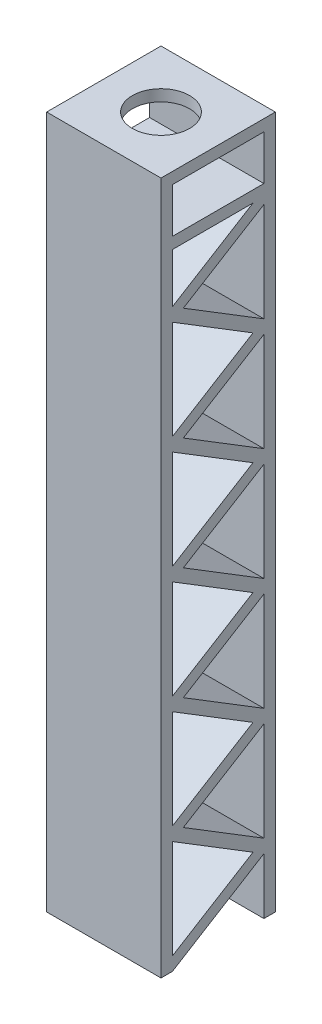
SolidWorks part; units mm, degrees
material "Corrugated Paper"
ref_plane "Front Plane" through (0, 0, 0) normal (0, 0, 1) x (1, 0, 0)
ref_plane "Top Plane" through (0, 0, 0) normal (0, 1, 0) x (1, 0, 0)
ref_plane "Right Plane" through (0, 0, 0) normal (1, 0, 0) x (0, 0, -1)
sketch "Sketch1" plane through (0, 0, 0) normal (1, 0, 0) x (0, 0, -1)
  line L0 (0, 135.6426) -> (0, -180.6532) construction
  line L2 (-25, -150) -> (-25, 150)
  line L3 (-25, 150) -> (25, 150)
  line L4 (25, -150) -> (25, 150)
  line L5 (15.2254, 120.4167) -> (-20, 120.4167)
  line L8 (-20, -147.0656) -> (-20, -103.7674)
  line L10 (20, -150) -> (20, -128.3511)
  line L11 (-20, -97.8986) -> (-20, -54.6008)
  line L13 (-20, 125.4167) -> (20, 125.4167)
  line L14 (-20, 125.4167) -> (-20, 145)
  line L15 (-20, 145) -> (20, 145)
  line L16 (20, 125.4167) -> (20, 145)
  line L23 (20, -73.3157) -> (20, -30.0179)
  line L26 (-20, 98.7678) -> (15.2254, 120.4167)
  line L27 (15.2254, 71.2497) -> (-20, 92.899)
  line L28 (-20, 49.6012) -> (15.2254, 71.2497)
  line L29 (15.2254, 22.0831) -> (-20, 43.7324)
  line L30 (-20, 0.4346) -> (15.2254, 22.0831)
  line L31 (15.2254, -27.0835) -> (-20, -5.4342)
  line L32 (-20, -48.732) -> (15.2254, -27.0835)
  line L33 (15.2254, -76.2501) -> (-20, -54.6008)
  line L34 (15.2254, -76.2501) -> (-20, -97.8986)
  line L35 (-20, -103.7674) -> (15.2254, -125.4167)
  line L36 (15.2254, -125.4167) -> (-20, -147.0656)
  line L38 (-15.2254, 95.8334) -> (20, 117.4819)
  line L39 (20, 74.1841) -> (-15.2254, 95.8334)
  line L40 (-15.2254, 46.6668) -> (20, 68.3153)
  line L41 (20, 25.0175) -> (-15.2254, 46.6668)
  line L42 (-15.2254, -2.4998) -> (20, 19.1487)
  line L43 (20, -24.1491) -> (-15.2254, -2.4998)
  line L44 (-15.2254, -51.6664) -> (20, -30.0179)
  line L45 (20, -73.3157) -> (-15.2254, -51.6664)
  line L46 (20, -79.1845) -> (-15.2254, -100.833)
  line L47 (-15.2254, -100.833) -> (20, -122.4823)
  line L48 (20, -128.3511) -> (-18.691, -152.1299)
  line L49 (-18.691, -152.1299) -> (-20, -152.9344)
  line L50 (-20, -152.9344) -> (-25, -152.9344)
  line L51 (-25, -152.9344) -> (-25, -150)
  line L53 (0, 199.6954) -> (0, 150) construction
  line L54 (20, -150) -> (20, -152.9344)
  line L55 (20, -152.9344) -> (25, -152.9344)
  line L56 (25, -152.9344) -> (25, -150)
  line L59 (20, -122.4823) -> (20, -79.1845)
  line L68 (-20, -48.732) -> (-20, -5.4342)
  line L69 (20, -24.1491) -> (20, 19.1487)
  line L74 (-20, 0.4346) -> (-20, 43.7324)
  line L75 (20, 25.0175) -> (20, 68.3153)
  line L80 (-20, 49.6012) -> (-20, 92.899)
  line L83 (20, 74.1841) -> (20, 117.4819)
  line L86 (-20, 98.7678) -> (-20, 120.4167)
  point P0 (0, 0)
  dimension "D1" = 50
  dimension "D2" = 300
  dimension "D3" = 5
  dimension "D4" = 5
  dimension "D5" = 5
  dimension "D6" = 5
extrude "Boss-Extrude1" add sketch "Sketch1" along normal mid plane 50
sketch "Sketch2" plane through (0, 150, 0) normal (0, 1, 0) x (1, 0, 0)
  circle A0 centre (0, 0) radius 12.5
  dimension "D1" = 25
extrude "Cut-Extrude1" cut sketch "Sketch2" against normal up to next
